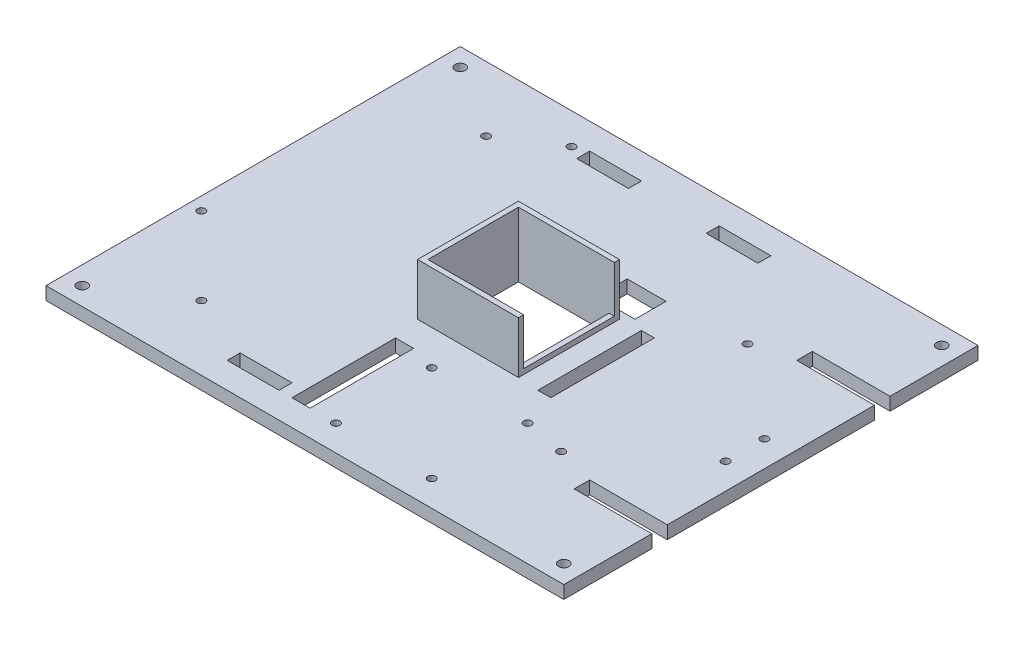
SolidWorks part; units mm, degrees
ref_plane "Front Plane" through (0, 0, 0) normal (0, 0, 1) x (1, 0, 0)
ref_plane "Top Plane" through (0, 0, 0) normal (0, 1, 0) x (1, 0, 0)
ref_plane "Right Plane" through (0, 0, 0) normal (1, 0, 0) x (0, 0, -1)
sketch "Sketch1" plane through (0, 0, 0) normal (0, 1, 0) x (1, 0, 0)
  line L1 (-100, 80) -> (100, 80)
  line L2 (-100, 80) -> (-100, -80)
  line L3 (-100, -80) -> (100, -80)
  line L4 (100, 80) -> (100, -80)
  line L5 (-100, 80) -> (100, -80) construction
  line L6 (-100, -80) -> (100, 80) construction
  point P0 (0, 0)
  dimension "D1" = 200
  dimension "D2" = 160
extrude "Boss-Extrude1" add sketch "Sketch1" along normal blind 5
sketch "Sketch2" plane through (0, 5, 0) normal (0, 1, 0) x (1, 0, 0)
  line L0 (-100, 0) -> (100, 0) construction
  line L1 (-100, 80) -> (-100, -80) construction
  line L2 (100, -80) -> (100, 80) construction
  line L4 (100, 80) -> (-100, 80) construction
  line L5 (0, 80) -> (0, -76.5866) construction
  circle A0 centre (-93, 73) radius 2
  circle A1 centre (93, 73) radius 2
  circle A2 centre (93, -73) radius 2
  circle A3 centre (-93, -73) radius 2
  dimension "D1" = 4
  dimension "D2" = 7
  dimension "D3" = 7
extrude "Cut-Extrude1" cut sketch "Sketch2" against normal blind 5
sketch "Sketch3" plane through (0, 5, 0) normal (0, 1, 0) x (1, 0, 0)
  line L0 (-100, 0) -> (110.5314, 0) construction
  line L1 (-100, 80) -> (-100, -80) construction
  line L2 (100, -80) -> (100, 80) construction
  line L3 (100, 80) -> (-100, 80) construction
  line L4 (0, 80) -> (0, -80) construction
  line L5 (-100, -80) -> (100, -80) construction
  circle A0 centre (90, 7.5) radius 1.5
  circle A1 centre (90, -7.5) radius 1.5
  dimension "D1" = 15
  dimension "D2" = 10
  dimension "D3" = 3
extrude "Cut-Extrude4" cut sketch "Sketch3" against normal blind 5
sketch "Sketch4" plane through (0, 5, 0) normal (0, 1, 0) x (1, 0, 0)
  line L0 (-100, 0) -> (119.321, 0) construction
  line L1 (-100, 80) -> (-100, -80) construction
  line L2 (100, -80) -> (100, 80) construction
  line L3 (100, 80) -> (-100, 80) construction
  line L4 (0, 80) -> (0, -80) construction
  line L5 (-100, -80) -> (100, -80) construction
  circle A0 centre (55, 36) radius 1.5
  circle A1 centre (55, -36) radius 1.5
  dimension "D1" = 45
  dimension "D2" = 3
  dimension "D3" = 72
extrude "Cut-Extrude5" cut sketch "Sketch4" against normal blind 5
sketch "Sketch5" plane through (0, 5, 0) normal (0, 1, 0) x (1, 0, 0)
  line L0 (-100, 0) -> (100, 0) construction
  line L1 (-100, 80) -> (-100, -80) construction
  line L2 (100, -80) -> (100, 80) construction
  line L4 (100, 80) -> (-100, 80) construction
  line L5 (0, 80) -> (0, -80) construction
  line L6 (-100, -80) -> (100, -80) construction
  line L7 (20, 17.5) -> (-15, 17.5)
  line L8 (20, 17.5) -> (20, -17.5)
  line L9 (20, -17.5) -> (-15, -17.5)
  line L10 (-15, 17.5) -> (-15, -17.5)
  line L11 (20, 17.5) -> (-15, -17.5) construction
  line L12 (20, -17.5) -> (-15, 17.5) construction
  point P6 (2.5, 0)
  dimension "D1" = 80
  dimension "D2" = 35
  dimension "D3" = 35
  dimension "D4" = 0
extrude "Cut-Extrude6" cut sketch "Sketch5" against normal blind 5
sketch "Sketch6" plane through (0, 5, 0) normal (0, 1, 0) x (1, 0, 0)
  line L0 (-98.249, 0) -> (100, 0) construction
  line L1 (100, -80) -> (100, 80) construction
  line L3 (-100, -80) -> (100, -80) construction
  line L4 (0, -80) -> (0, 80) construction
  line L5 (100, 80) -> (-100, 80) construction
sketch "Sketch7" plane through (0, 5, 0) normal (0, 1, 0) x (1, 0, 0)
  line L0 (-100, -80) -> (100, -80) construction
  line L1 (-15, -30) -> (-8, -30)
  line L2 (-15, -30) -> (-15, -70)
  line L3 (-15, -70) -> (-8, -70)
  line L4 (-8, -30) -> (-8, -70)
  line L5 (100, -80) -> (100, 80) construction
  line L6 (-98.249, 0) -> (100, 0) construction
  line L7 (30, 20) -> (35, 20)
  line L8 (30, 20) -> (30, -20)
  line L9 (30, -20) -> (35, -20)
  line L10 (35, 20) -> (35, -20)
  line L11 (30, 20) -> (35, -20) construction
  line L12 (30, -20) -> (35, 20) construction
  line L13 (-98.249, 0) -> (100, 0) construction
  line L14 (-100, 80) -> (-100, -80) construction
  line L15 (-40, 70) -> (-20, 70)
  line L16 (-40, 70) -> (-40, 65)
  line L17 (-40, 65) -> (-20, 65)
  line L18 (-20, 70) -> (-20, 65)
  line L19 (-40, 70) -> (-20, 65) construction
  line L20 (-40, 65) -> (-20, 70) construction
  line L21 (100, 80) -> (-100, 80) construction
  line L22 (-40, -65) -> (-20, -65)
  line L23 (-20, -70) -> (-20, -65)
  line L24 (-40, -70) -> (-40, -65)
  line L25 (-40, -70) -> (-20, -70)
  point P8 (32.5, 0)
  point P25 (-30, 67.5)
  dimension "D1" = 7
  dimension "D2" = 40
  dimension "D3" = 10
  dimension "D4" = 108
  dimension "D5" = 5
  dimension "D6" = 70
  dimension "D7" = 40
  dimension "D10" = 60
  dimension "D11" = 20
  dimension "D12" = 12.5
  dimension "D13" = 5
extrude "Cut-Extrude7" cut sketch "Sketch7" against normal blind 5
sketch "Sketch8" plane through (0, 5, 0) normal (0, 1, 0) x (1, 0, 0)
  line L0 (20, 17.5) -> (-15, 17.5) construction
  line L1 (10, 34.5) -> (25, 34.5)
  line L2 (10, 34.5) -> (10, 22.5)
  line L3 (10, 22.5) -> (25, 22.5)
  line L4 (25, 34.5) -> (25, 22.5)
  line L5 (10, 34.5) -> (25, 22.5) construction
  line L6 (10, 22.5) -> (25, 34.5) construction
  line L7 (100, -80) -> (100, 80) construction
  line L8 (-98.249, 0) -> (100, 0) construction
  line L9 (100, 46) -> (70, 46)
  line L10 (100, 46) -> (100, 40)
  line L11 (100, 40) -> (70, 40)
  line L12 (70, 46) -> (70, 40)
  line L13 (100, -46) -> (100, -40)
  line L14 (70, -46) -> (70, -40)
  line L15 (100, -40) -> (70, -40)
  line L16 (100, -46) -> (70, -46)
  point P0 (17.5, 28.5)
  dimension "D1" = 12
  dimension "D2" = 15
  dimension "D3" = 5
  dimension "D4" = 75
  dimension "D5" = 6
  dimension "D6" = 40
  dimension "D7" = 30
extrude "Cut-Extrude8" cut sketch "Sketch8" against normal blind 5
sketch "Sketch9" plane through (0, 5, 0) normal (0, 1, 0) x (1, 0, 0)
  line L0 (100, 46) -> (100, 80) construction
  line L1 (10, 70) -> (30, 70)
  line L2 (10, 70) -> (10, 65)
  line L3 (10, 65) -> (30, 65)
  line L4 (30, 70) -> (30, 65)
  line L5 (100, 80) -> (-100, 80) construction
  point P4 (100, 63)
  dimension "D1" = 20
  dimension "D2" = 5
  dimension "D3" = 70
  dimension "D4" = 10
extrude "Cut-Extrude9" cut sketch "Sketch9" against normal blind 5
sketch "Sketch10" plane through (0, 5, 0) normal (0, 1, 0) x (1, 0, 0)
  line L0 (-100, -80) -> (100, -80) construction
  line L1 (-100, 80) -> (-100, -80) construction
  line L2 (100, 80) -> (-100, 80) construction
  circle A0 centre (-95, -25) radius 1.5
  circle A1 centre (-45, 68) radius 1.5
  dimension "D1" = 55
  dimension "D2" = 3
  dimension "D3" = 5
  dimension "D4" = 3
  dimension "D5" = 12
  dimension "D6" = 55
extrude "Cut-Extrude10" cut sketch "Sketch10" against normal blind 5
sketch "Sketch11" plane through (0, 5, 0) normal (0, 1, 0) x (1, 0, 0)
  line L0 (-8, -70) -> (-8, -30) construction
  line L1 (-100, -80) -> (100, -80) construction
  line L2 (2, -51.5) -> (59.0967, -51.5) construction
  line L3 (20.5, -24.2001) -> (20.5, -71.6632) construction
  circle A0 centre (2, -33) radius 1.5
  circle A1 centre (2, -70) radius 1.5
  circle A2 centre (39, -70) radius 1.5
  circle A3 centre (39, -33) radius 1.5
  dimension "D1" = 10
  dimension "D2" = 47
  dimension "D3" = 3
  dimension "D4" = 18.5
  dimension "D5" = 18.5
extrude "Cut-Extrude11" cut sketch "Sketch11" against normal blind 5
sketch "Sketch12" plane through (0, 5, 0) normal (0, 1, 0) x (1, 0, 0)
  line L0 (-65, 80) -> (-65, -83.2106) construction
  line L1 (100, 80) -> (-100, 80) construction
  line L2 (-100, 80) -> (-100, -80) construction
  line L3 (-98.249, 0) -> (104.7756, 0) construction
  circle A0 centre (-65, 55) radius 1.5
  circle A1 centre (-65, -55) radius 1.5
  dimension "D3" = 3
  dimension "D1" = 35
  dimension "D2" = 25
extrude "Cut-Extrude12" cut sketch "Sketch12" against normal blind 5
sketch "Sketch14" plane through (0, 5, 0) normal (0, 1, 0) x (1, 0, 0)
  line L7 (-98.249, 0) -> (100, 0) construction
  line L8 (-15, 17.5) -> (-17, 17.5)
  line L9 (-15, 17.5) -> (-15, -17.5)
  line L10 (-15, -17.5) -> (-17, -17.5)
  line L11 (-17, 17.5) -> (-17, -17.5)
  line L12 (-15, 17.5) -> (-17, -17.5) construction
  line L13 (-15, -17.5) -> (-17, 17.5) construction
  line L21 (20, 17.5) -> (22, 17.5)
  line L22 (20, 17.5) -> (20, -17.5)
  line L23 (20, -17.5) -> (22, -17.5)
  line L24 (22, 17.5) -> (22, -17.5)
  line L25 (20, 17.5) -> (22, -17.5) construction
  line L26 (20, -17.5) -> (22, 17.5) construction
  line L27 (-15, 17.5) -> (-15, -17.5) construction
  line L29 (20, -17.5) -> (20, 17.5) construction
  point P7 (-16, 0)
  point P19 (21, 0)
  dimension "D1" = 2
  dimension "D3" = 2
  dimension "D6" = 0
  dimension "D8" = 35
  dimension "D9" = 0
  dimension "D10" = 35
extrude "Boss-Extrude3" add sketch "Sketch14" along normal blind 20
sketch "Sketch15" plane through (0, 5, 0) normal (0, 1, 0) x (1, 0, 0)
  line L1 (-17, -17.5) -> (22, -17.5)
  line L2 (-17, -17.5) -> (-17, -19.5)
  line L3 (-17, -19.5) -> (22, -19.5)
  line L4 (22, -17.5) -> (22, -19.5)
  dimension "D1" = 39
  dimension "D2" = 2
extrude "Boss-Extrude4" add sketch "Sketch15" along normal blind 20
sketch "Sketch16" plane through (0, 5, 0) normal (0, 1, 0) x (1, 0, 0)
  line L1 (-17, 17.5) -> (22, 17.5)
  line L2 (-17, 17.5) -> (-17, 19.5)
  line L3 (-17, 19.5) -> (22, 19.5)
  line L4 (22, 17.5) -> (22, 19.5)
  dimension "D1" = 39
  dimension "D2" = 2
extrude "Boss-Extrude5" add sketch "Sketch16" along normal blind 20
sketch "Sketch17" plane through (22, 0, 0) normal (1, 0, 0) x (0, 0, -1)
  line L0 (-19.5, 25) -> (19.5, 25) construction
  line L1 (-17.5, 25) -> (17.5, 25)
  line L2 (-17.5, 25) -> (-17.5, 7)
  line L3 (-17.5, 7) -> (17.5, 7)
  line L4 (17.5, 25) -> (17.5, 7)
  line L5 (-19.5, 25) -> (-19.5, 5) construction
  line L6 (19.5, 25) -> (19.5, 5) construction
  line L7 (-80, 5) -> (80, 5) construction
  dimension "D1" = 0
  dimension "D2" = 2
  dimension "D3" = 2
  dimension "D4" = 2
extrude "Cut-Extrude13" cut sketch "Sketch17" against normal blind 20
sketch "Sketch18" plane through (0, 0, 19.5) normal (0, 0, 1) x (1, 0, 0)
